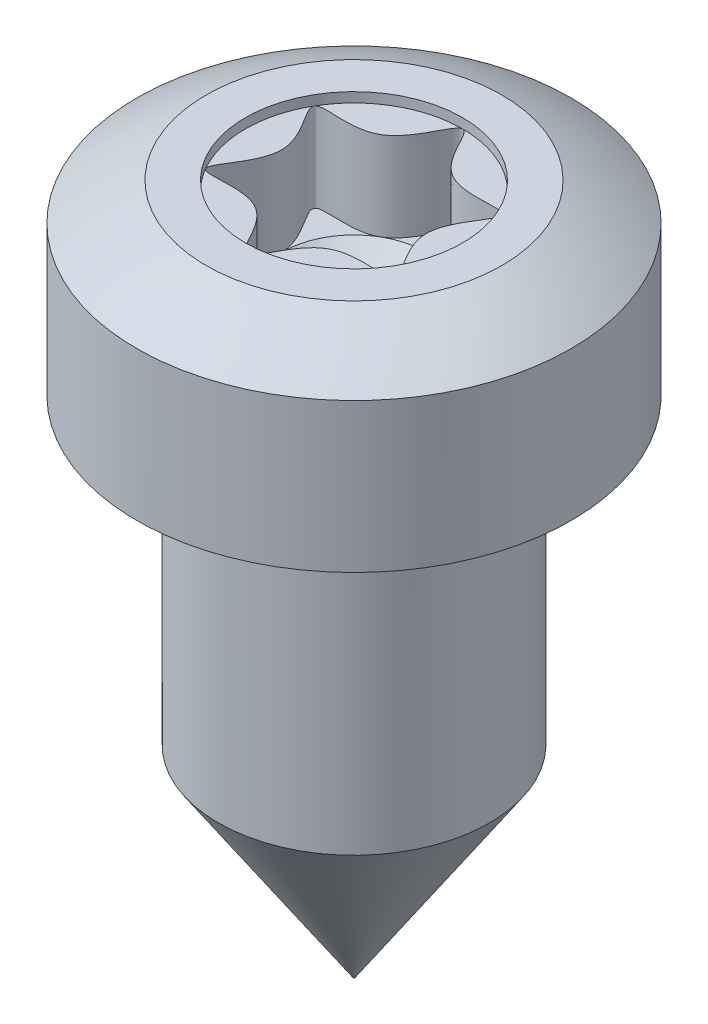
SolidWorks part; units mm, degrees
ref_plane "Front" through (0, 0, 0) normal (0, 0, 1) x (1, 0, 0)
ref_plane "Top" through (0, 0, 0) normal (0, 1, 0) x (1, 0, 0)
ref_plane "Right" through (0, 0, 0) normal (1, 0, 0) x (0, 0, -1)
sketch "Sketch1" plane through (0, 0, 0) normal (0, 0, 1) x (1, 0, 0)
  line L0 (0, 0) -> (0, 9.001) construction
  line L1 (0, 0) -> (0, 8.9)
  line L2 (0, 8.9) -> (2.8, 8.9)
  line L3 (2.8, 8.9) -> (2.8, 6.5)
  line L4 (2.8, 6.5) -> (1.75, 6.5)
  line L5 (1.75, 6.5) -> (1.75, 0)
  line L6 (1.75, 0) -> (0, 0)
  line L7 (0, 8.9) -> (-1.1, 8.9) construction
  line L8 (2.8, 6.5) -> (2.8, 5.4) construction
  line L9 (0, 0) -> (1.75, 2.6) construction
  dimension "head_dia" = 5.6
  dimension "head_ht" = 2.4
  dimension "length" = 6.5
  dimension "dia" = 3.5
  dimension "pitch" = 1.1
  dimension "thread_gap" = 1.1
  dimension "end_length" = 2.6
revolve "Body-Revolve" add sketch "Sketch1" angle 360 about L1
cosmetic thread "ThreadCosmetic" [suppressed] parameters "D1"=5.4, "D2"=2.3092
sketch "Sketch3" plane through (0, 0, 0) normal (0, 0, 1) x (1, 0, 0)
  line L0 (2.8, 8.42) -> (0, 4.2775) construction
  line L2 (2.8, 6.5) -> (2.8, 8.9) construction
  line L3 (0, 0) -> (0, 8.9) construction
  line L4 (2.8, 8.9) -> (-2.8, 8.9) construction
  line L5 (0, 9.2775) -> (0, 10.4044)
  line L6 (0, 10.4044) -> (5, 10.4044)
  line L7 (5, 10.4044) -> (5, 4.2775)
  arc A0 (5, 4.2775) -> (0, 9.2775) centre (0, 4.2775) ccw
  dimension "sphere_rad" = 5
  dimension "D1" = 0.48
  dimension "D2" = 1.1268
revolve "Head-Cut-Revolve" cut sketch "Sketch3" angle 360 about axis through (0, 0, 0) along (0, 1, 0)
sketch "Sketch4" plane through (0, 8.9, 0) normal (0, 1, 0) x (-1, 0, 0)
  line L0 (0, 0) -> (0, -1.54)
  line L1 (0, 0) -> (-0.7, -1.2124)
  circle A0 centre (0, 0) radius 1.4
  circle A1 centre (0, 0) radius 0.9333
  spline S0 degree 3 poles (0.302, -0.523) (0, -1.8385) (-0.302, -0.523) (-1.5922, -0.9193) (-0.6039, 0) (-1.5922, 0.9193) (-0.302, 0.523) (0, 1.8385) (0.302, 0.523) (1.5922, 0.9193) (0.6039, 0) (1.5922, -0.9193) (0.302, -0.523) (0, -1.8385) (-0.302, -0.523) knots -0.25 -0.166667 -0.083333 0 0.083333 0.166667 0.25 0.333333 0.416667 0.5 0.583333 0.666667 0.75 0.833333 0.916667 1 1.083333 1.166667 1.25 only from (0, -1.4) to (0, -1.4)
  point P4 (0, -1.4)
  point P7 (-0.4667, -0.8083)
  point P10 (-1.2124, -0.7)
  point P11 (-1.2124, 0.7)
  point P12 (0, 1.4)
  point P13 (1.2124, 0.7)
  point P14 (1.2124, -0.7)
  point P15 (-0.9333, 0)
  point P16 (-0.4667, 0.8083)
  point P17 (0.4667, 0.8083)
  point P18 (0.9333, 0)
  point P19 (0.4667, -0.8083)
  dimension "socket-dia" = 2.8
  dimension "D1" = 1.8667
  dimension "D2" = 30
  dimension "D3" = 1.54
extrude "Recess-Cut-Extrude1" cut sketch "Sketch4" against normal blind 1.27 contours S0
sketch "Sketch5" plane through (0, 8.9, 0) normal (0, 1, 0) x (-1, 0, 0)
  circle A0 centre (0, 0) radius 1.4
  dimension "D1" = 2.8
extrude "Recess-Cut-Extrude2" cut sketch "Sketch5" against normal blind 0.127
sketch "Sketch6" plane through (0, 0, 0) normal (0, 0, 1) x (1, 0, 0)
  line L0 (0, 7.63) -> (0.9333, 7.63)
  line L2 (0, 0) -> (0, 8.9) construction
  line L4 (1.2177, 7.63) -> (-1.2177, 7.63) construction
  line L5 (0.9333, 7.63) -> (0, 6.74)
  line L6 (0, 6.74) -> (0, 7.63)
  line L7 (1.4, 8.9) -> (-1.4, 8.9) construction
  dimension "D1" = 2.16
  dimension "D2" = 0.9333
revolve "Drill-Cut-Revolve" cut sketch "Sketch6" angle 360 about axis through (0, 0, 0) along (0, 1, 0)
fillet "Fillet1" radius 0.1 1 edges at (0, 6.5, -1.75)
sketch "Sketch7" plane through (0, 0, 0) normal (0, 0, 1) x (1, 0, 0)
  line L0 (1.75, 0) -> (1.75, 2.6)
  line L1 (1.75, 0) -> (1.75, 6.4) construction
  line L2 (1.75, 2.6) -> (0.01, 0)
  line L3 (-1.75, 0) -> (1.75, 0) construction
  line L4 (0.01, 0) -> (1.75, 0)
  dimension "D1" = 0.01
  dimension "D2" = 2.6
revolve "Body-Cut-Revolve" cut sketch "Sketch7" angle 360 about axis through (0, 0, 0) along (0, 1, 0)
sketch "Sketch8" plane through (0, 0, 0) normal (0, 0, 1) x (1, 0, 0)
  line L0 (1.75, 5.4) -> (1.75, 4.7125)
  line L1 (1.75, 2.6) -> (1.75, 6.4) construction
  line L2 (1.75, 4.7125) -> (1.1546, 5.0563)
  line L3 (1.1546, 5.0563) -> (1.75, 5.4)
  line L4 (-2.8, 6.5) -> (2.8, 6.5) construction
  line L5 (0, 0) -> (0, 8.9) construction
  dimension "D1" = 1.1
  dimension "D2" = 1.1546
revolve "ThreadSchematic" [suppressed] cut sketch "Sketch8" angle 360 about axis through (0, 0, 0) along (0, 1, 0)
pattern_linear "ThdSchPat" [suppressed] count 5 spacing 1.1 along (0, 1, 0)
equation "\"D1@ThreadCosmetic\" = \"length@Sketch1\" - \"thread_gap@Sketch1\""
equation "\"D2@ThreadCosmetic\" = \"dia@Sketch1\" - \"pitch@Sketch1\" * 1.0825"
equation "\"D1@Sketch3\" = 0.2 * \"head_ht@Sketch1\""
equation "\"D1@Sketch4\" = \"socket-dia@Sketch4\" / 1.5"
equation "\"D3@Sketch4\" = \"socket-dia@Sketch4\" / 2 * 1.1"
equation "\"D1@Sketch5\" = \"socket-dia@Sketch4\""
equation "\"D1@Recess-Cut-Extrude2\" = 0.1 * \"socket-dep@Recess-Cut-Extrude1\""
equation "\"D1@Sketch6\" = 0.9 * \"head_ht@Sketch1\""
equation "\"D2@Sketch6\" = \"D1@Sketch4\" / 2"
equation "\"D2@Sketch7\" = \"end_length@Sketch1\""
equation "\"D1@Sketch8\" = \"thread_gap@Sketch1\""
equation "\"D2@Sketch8\" = \"D2@ThreadCosmetic\" / 2"
equation "\"D3@ThdSchPat\" = \"pitch@Sketch1\""
equation "\"D1@ThdSchPat\" =  ( \"length@Sketch1\" - \"thread_gap@Sketch1\" )  / \"pitch@Sketch1\""
